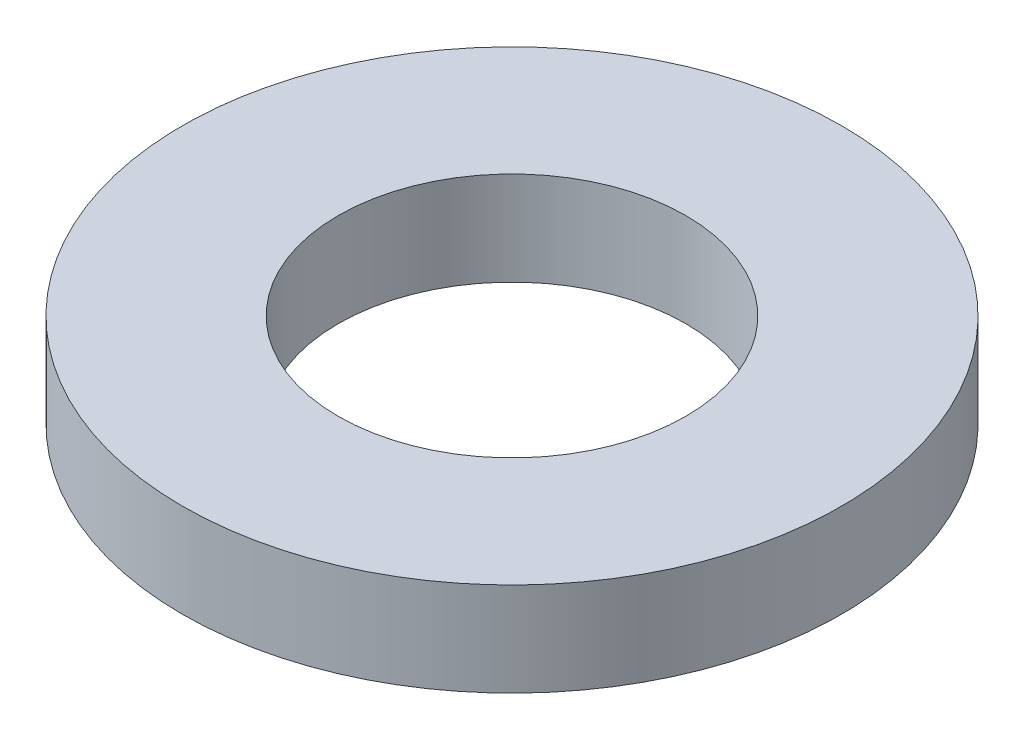
SolidWorks part; units mm, degrees
ref_plane "Front Plane" through (0, 0, 0) normal (0, 0, 1) x (1, 0, 0)
ref_plane "Top Plane" through (0, 0, 0) normal (0, 1, 0) x (1, 0, 0)
ref_plane "Right Plane" through (0, 0, 0) normal (1, 0, 0) x (0, 0, -1)
sketch "Sketch1" plane through (0, 0, 0) normal (0, 1, 0) x (1, 0, 0)
  circle A0 centre (0, 0) radius 3.5188
  dimension "D1" = 7.0375
extrude "Boss-Extrude1" add sketch "Sketch1" along normal blind 1
sketch "Sketch2" plane through (0, 1, 0) normal (0, 1, 0) x (1, 0, 0)
  circle A0 centre (0, 0) radius 1.8562
  dimension "D1" = 3.7125
extrude "Cut-Extrude1" cut sketch "Sketch2" against normal through all
